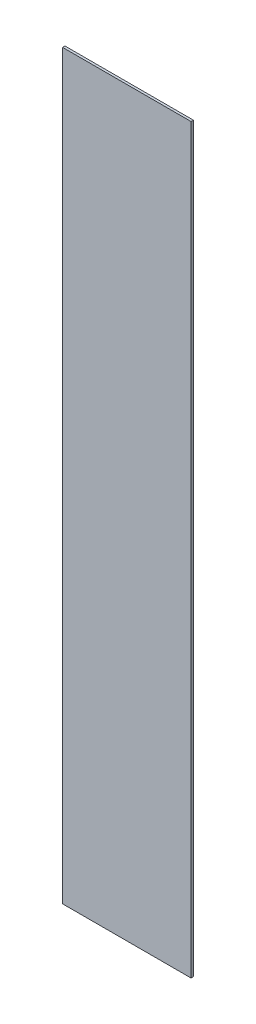
SolidWorks part; units mm, degrees
material "AISI 4340 Steel, annealed"
ref_plane "Front Plane" through (0, 0, 0) normal (0, 0, 1) x (1, 0, 0)
ref_plane "Top Plane" through (0, 0, 0) normal (0, 1, 0) x (1, 0, 0)
ref_plane "Right Plane" through (0, 0, 0) normal (1, 0, 0) x (0, 0, -1)
sketch "Sketch1" plane through (0, 0, 0) normal (0, 0, 1) x (1, 0, 0)
  line L1 (-135, 780) -> (135, 780)
  line L2 (-135, 780) -> (-135, -780)
  line L3 (-135, -780) -> (135, -780)
  line L4 (135, 780) -> (135, -780)
  line L5 (-135, 780) -> (135, -780) construction
  line L6 (-135, -780) -> (135, 780) construction
  point P0 (0, 0)
  dimension "D1" = 270
  dimension "D2" = 1560
extrude "Plate extrude" add sketch "Sketch1" along normal blind 5
